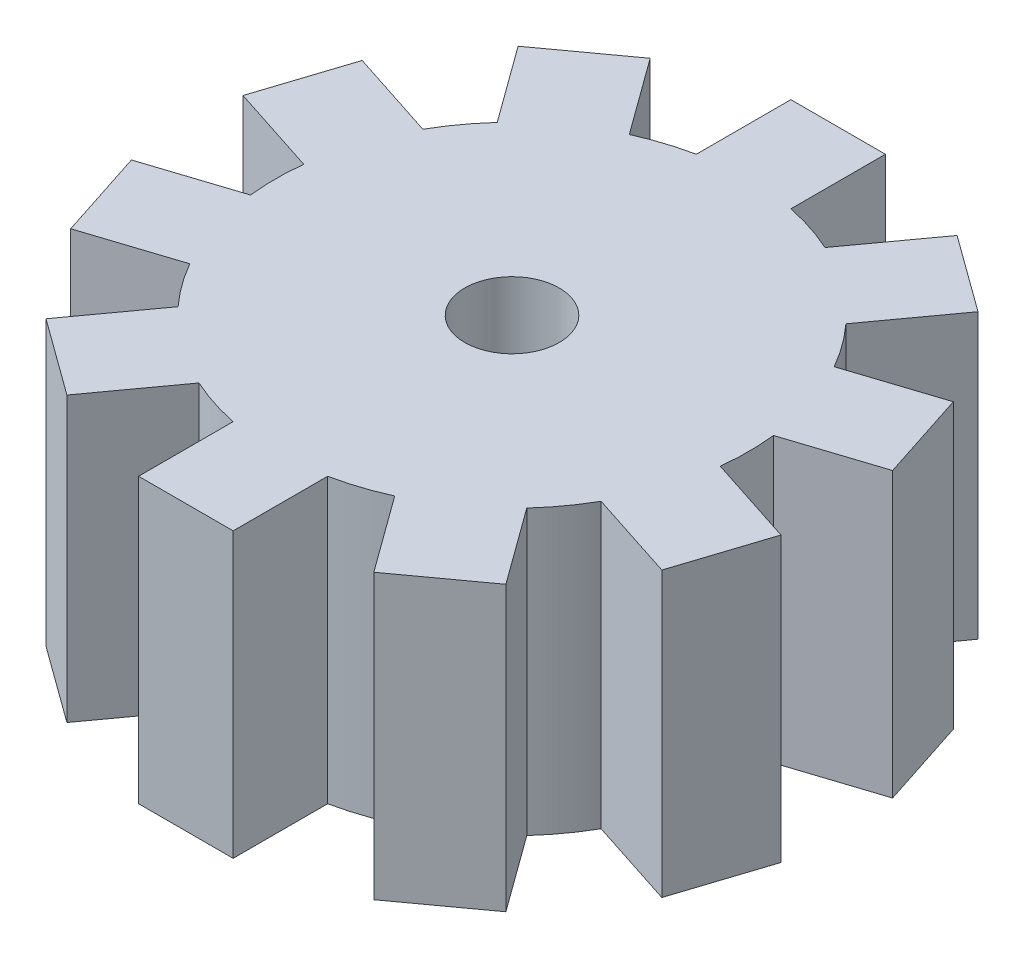
SolidWorks part; units mm, degrees
ref_plane "前基準面" through (0, 0, 0) normal (0, 0, 1) x (1, 0, 0)
ref_plane "上基準面" through (0, 0, 0) normal (0, 1, 0) x (1, 0, 0)
ref_plane "右基準面" through (0, 0, 0) normal (1, 0, 0) x (0, 0, -1)
sketch "草圖1" plane through (0, 0, 0) normal (0, 1, 0) x (1, 0, 0)
  line L0 (0, -24.955) -> (0, 42.2387) construction
  line L1 (-33.5321, 0) -> (41.1211, 0) construction
  line L2 (24.3207, 24.968) -> (16.2305, 30.8459)
  line L3 (5, 34.4949) -> (-5, 34.4949)
  line L4 (5, 34.4949) -> (5, 24.4949)
  line L6 (-5, 34.4949) -> (-5, 24.4949)
  line L7 (0, 24.955) -> (0, 34.4949) construction
  line L8 (5, 29.4949) -> (-5, 29.4949) construction
  line L9 (24.3207, 24.968) -> (18.4428, 16.8779)
  line L11 (16.2305, 30.8459) -> (10.3527, 22.7557)
  line L12 (14.6682, 20.189) -> (20.2756, 27.907) construction
  line L13 (21.3818, 20.9229) -> (13.2916, 26.8008) construction
  line L14 (34.3517, 5.9042) -> (31.2615, 15.4148)
  line L15 (34.3517, 5.9042) -> (24.8411, 2.8141)
  line L17 (31.2615, 15.4148) -> (21.7509, 12.3246)
  line L18 (23.7764, 7.7254) -> (28.4889, 9.2566) construction
  line L19 (29.5964, 4.3591) -> (26.5062, 13.8697) construction
  line L20 (31.2615, -15.4148) -> (34.3517, -5.9042)
  line L21 (31.2615, -15.4148) -> (21.7509, -12.3246)
  line L23 (34.3517, -5.9042) -> (24.8411, -2.8141)
  line L24 (28.0513, -9.1144) -> (28.4889, -9.2566) construction
  line L25 (26.5062, -13.8697) -> (29.5964, -4.3591) construction
  line L26 (16.2305, -30.8459) -> (24.3207, -24.968)
  line L27 (16.2305, -30.8459) -> (10.3527, -22.7557)
  line L29 (24.3207, -24.968) -> (18.4428, -16.8779)
  line L30 (17.3367, -23.8619) -> (17.6071, -24.2341) construction
  line L31 (13.2916, -26.8008) -> (21.3818, -20.9229) construction
  line L32 (-5, -34.4949) -> (5, -34.4949)
  line L33 (-5, -34.4949) -> (-5, -24.4949)
  line L35 (5, -34.4949) -> (5, -24.4949)
  line L36 (0, -24.955) -> (0, -25) construction
  line L37 (-5, -29.4949) -> (5, -29.4949) construction
  line L38 (-24.3207, -24.968) -> (-16.2305, -30.8459)
  line L39 (-24.3207, -24.968) -> (-18.4428, -16.8779)
  line L41 (-16.2305, -30.8459) -> (-10.3527, -22.7557)
  line L42 (-14.6682, -20.189) -> (-14.6946, -20.2254) construction
  line L43 (-21.3818, -20.9229) -> (-13.2916, -26.8008) construction
  line L44 (-34.3517, -5.9042) -> (-31.2615, -15.4148)
  line L45 (-34.3517, -5.9042) -> (-24.8411, -2.8141)
  line L47 (-31.2615, -15.4148) -> (-21.7509, -12.3246)
  line L48 (-23.7336, -7.7115) -> (-32.8066, -10.6595) construction
  line L49 (-29.5964, -4.3591) -> (-26.5062, -13.8697) construction
  line L50 (-31.2615, 15.4148) -> (-34.3517, 5.9042)
  line L51 (-31.2615, 15.4148) -> (-21.7509, 12.3246)
  line L53 (-34.3517, 5.9042) -> (-24.8411, 2.8141)
  line L54 (-23.7336, 7.7115) -> (-32.8066, 10.6595) construction
  line L55 (-26.5062, 13.8697) -> (-29.5964, 4.3591) construction
  line L56 (-16.2305, 30.8459) -> (-24.3207, 24.968)
  line L57 (-16.2305, 30.8459) -> (-10.3527, 22.7557)
  line L59 (-24.3207, 24.968) -> (-18.4428, 16.8779)
  line L60 (-14.6682, 20.189) -> (-14.6946, 20.2254) construction
  line L61 (-13.2916, 26.8008) -> (-21.3818, 20.9229) construction
  line L64 (-17.3367, 23.8619) -> (-17.6071, 24.2341) construction
  line L65 (0, -29.4949) -> (0, -29.955) construction
  line L66 (-17.3367, -23.8619) -> (-17.6071, -24.2341) construction
  arc A0 (-21.7509, -12.3246) -> (-18.4428, -16.8779) centre (0, 0) ccw
  arc A1 (-24.8411, 2.8141) -> (-24.8411, -2.8141) centre (0, 0) ccw
  arc A2 (-18.4428, 16.8779) -> (-21.7509, 12.3246) centre (0, 0) ccw
  arc A3 (-5, 24.4949) -> (-10.3527, 22.7557) centre (0, 0) ccw
  arc A4 (10.3527, 22.7557) -> (5, 24.4949) centre (0, 0) ccw
  arc A5 (21.7509, 12.3246) -> (18.4428, 16.8779) centre (0, 0) ccw
  arc A6 (24.8411, -2.8141) -> (24.8411, 2.8141) centre (0, 0) ccw
  arc A7 (18.4428, -16.8779) -> (21.7509, -12.3246) centre (0, 0) ccw
  arc A8 (5, -24.4949) -> (10.3527, -22.7557) centre (0, 0) ccw
  arc A9 (-10.3527, -22.7557) -> (-5, -24.4949) centre (0, 0) ccw
  circle A10 centre (0, 0) radius 5
  point P7 (0, 29.4949)
  point P13 (17.3367, 23.8619)
  point P25 (28.0513, 9.1144)
  point P34 (28.0513, -9.1144)
  point P43 (17.3367, -23.8619)
  point P52 (0, -29.4949)
  point P63 (-17.3367, -23.8619)
  point P72 (-28.0513, -9.1144)
  point P81 (-28.0513, 9.1144)
  point P90 (-17.3367, 23.8619)
  point P99 (0, 0)
  dimension "D1" = 50
  dimension "D5" = 10
  dimension "D2" = 10
  dimension "D3" = 10
  dimension "D4" = 10
extrude "填料-伸長1" add sketch "草圖1" along normal blind 30
